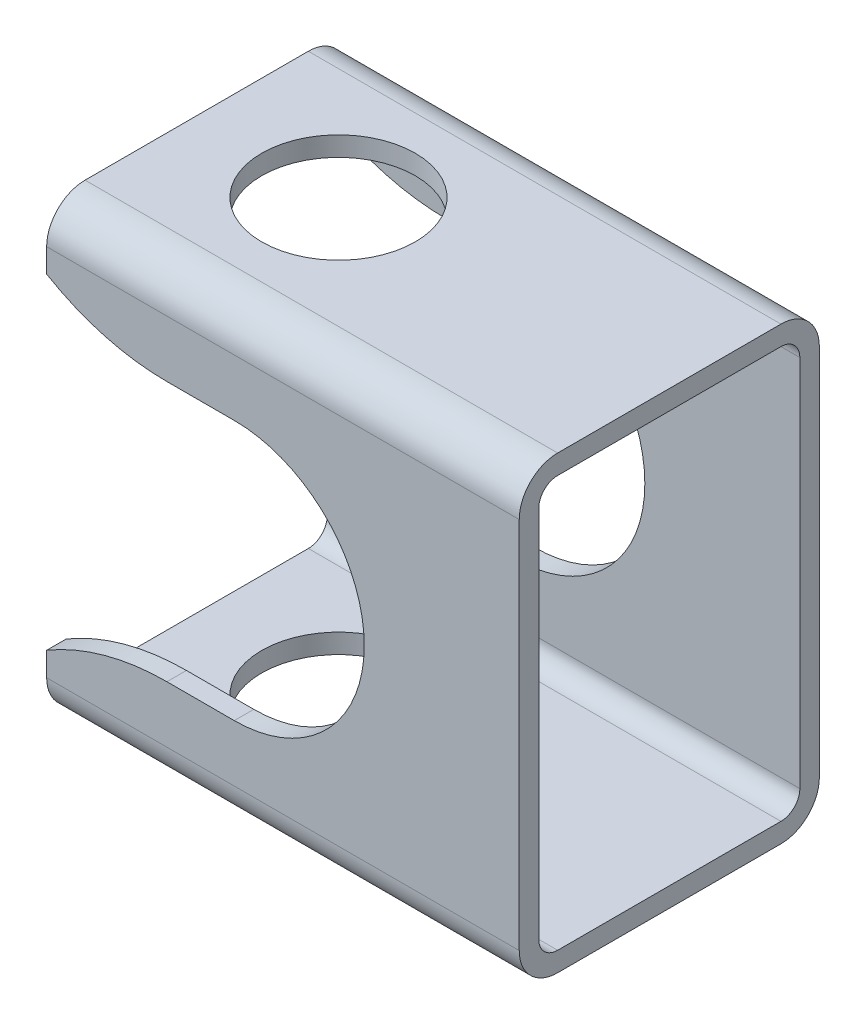
SolidWorks part; units mm, degrees
ref_plane "Front Plane" through (0, 0, 0) normal (0, 0, 1) x (1, 0, 0)
ref_plane "Top Plane" through (0, 0, 0) normal (0, 1, 0) x (1, 0, 0)
ref_plane "Right Plane" through (0, 0, 0) normal (1, 0, 0) x (0, 0, -1)
sketch "Sketch1" plane through (0, 0, 0) normal (0, 1, 0) x (1, 0, 0)
  line L0 (0, 0) -> (40, 0)
  dimension "D1" = 40
other "Fsae chassis 1_5 X 1 INCH RECT(1)"
ref_plane "Plane2" through (0, 0, 0) normal (1, 0, 0) x (0, 0, -1)
sketch "Sketch15" plane through (0, 0, 0) normal (1, 0, 0) x (0, 0, -1)
  line L1 (-9.4488, -17.399) -> (9.4488, -17.399)
  line L2 (-11.049, -15.7988) -> (-11.049, 15.7988)
  line L3 (-9.4488, 17.399) -> (9.4488, 17.399)
  line L4 (11.049, -15.7988) -> (11.049, 15.7988)
  line L5 (-11.049, -17.399) -> (11.049, 17.399) construction
  line L6 (-11.049, 17.399) -> (11.049, -17.399) construction
  line L7 (-9.4488, 19.05) -> (9.4488, 19.05)
  line L8 (-12.7, 15.7988) -> (-12.7, -15.7988)
  line L9 (-9.4488, -19.05) -> (9.4488, -19.05)
  line L10 (12.7, 15.7988) -> (12.7, -15.7988)
  arc A0 (-12.7, -15.7988) -> (-9.4488, -19.05) centre (-9.4488, -15.7988) ccw
  arc A1 (9.4488, -19.05) -> (12.7, -15.7988) centre (9.4488, -15.7988) ccw
  arc A2 (12.7, 15.7988) -> (9.4488, 19.05) centre (9.4488, 15.7988) ccw
  arc A3 (-12.7, 15.7988) -> (-9.4488, 19.05) centre (-9.4488, 15.7988) cw
  arc A4 (9.4488, 17.399) -> (11.049, 15.7988) centre (9.4488, 15.7988) cw
  arc A5 (11.049, -15.7988) -> (9.4488, -17.399) centre (9.4488, -15.7988) cw
  arc A6 (-9.4488, -17.399) -> (-11.049, -15.7988) centre (-9.4488, -15.7988) cw
  arc A7 (-11.049, 15.7988) -> (-9.4488, 17.399) centre (-9.4488, 15.7988) cw
  point P0 (0, 0)
  point P5 (0, 0)
  point P10 (-12.7, 0)
  point P11 (12.7, 0)
  point P12 (0, -19.05)
  point P13 (0, 19.05)
  point P30 (0, 0)
  dimension "D3" = 3.2512
  dimension "D4" = 25.4
  dimension "D1" = 38.1
  dimension "D2" = 1.651
sketch "Sketch16" plane through (0, 0, -12.7) normal (0, 0, -1) x (-1, 0, 0)
  line L0 (0, 0) -> (-15.88, 0) construction
  line L1 (0, -15.7988) -> (0, 15.7988) construction
  line L2 (-15.88, 11) -> (-10.18, 11)
  line L3 (-15.88, -11) -> (-10.18, -11)
  line L4 (0, 13.7847) -> (0, -13.7847)
  arc A0 (-15.88, 11) -> (-15.88, -11) centre (-15.88, 0) ccw
  arc A1 (-10.18, 11) -> (0, 13.7847) centre (-10.18, 31) ccw
  arc A2 (-10.18, -11) -> (0, -13.7847) centre (-10.18, -31) cw
  dimension "D2" = 11
  dimension "D4" = 20
  dimension "D1" = 15.88
  dimension "D3" = 5.7
extrude "Cut-Extrude1" cut sketch "Sketch16" against normal through all both and the other way through all
sketch "Sketch19" plane through (0, 19.05, 0) normal (0, 1, 0) x (1, 0, 0)
  line L0 (0, 0) -> (12, 0) construction
  point P1 (12, 0)
  dimension "D1" = 12
hole_wizard "Ø13.0 (13) Diameter Hole2" positions "Sketch19" profile "Sketch20" hole size "Ø13.0" standard "ANSI Metric" end condition through all
sketch "Sketch20" plane through (12, 19.05, 0) normal (1, 0, 0) x (0, 0, 1)
  line L0 (0, 0) -> (0, 38.1)
  line L1 (0, 38.1) -> (6.5, 38.1)
  line L2 (6.5, 38.1) -> (6.5, 0)
  line L5 (6.5, 0) -> (0, 0)
  line L11 (0, -6.35) -> (0, 107.95) construction
  dimension "Thru Hole Dia." = 13
  dimension "Thru Hole Depth" = 38.1
